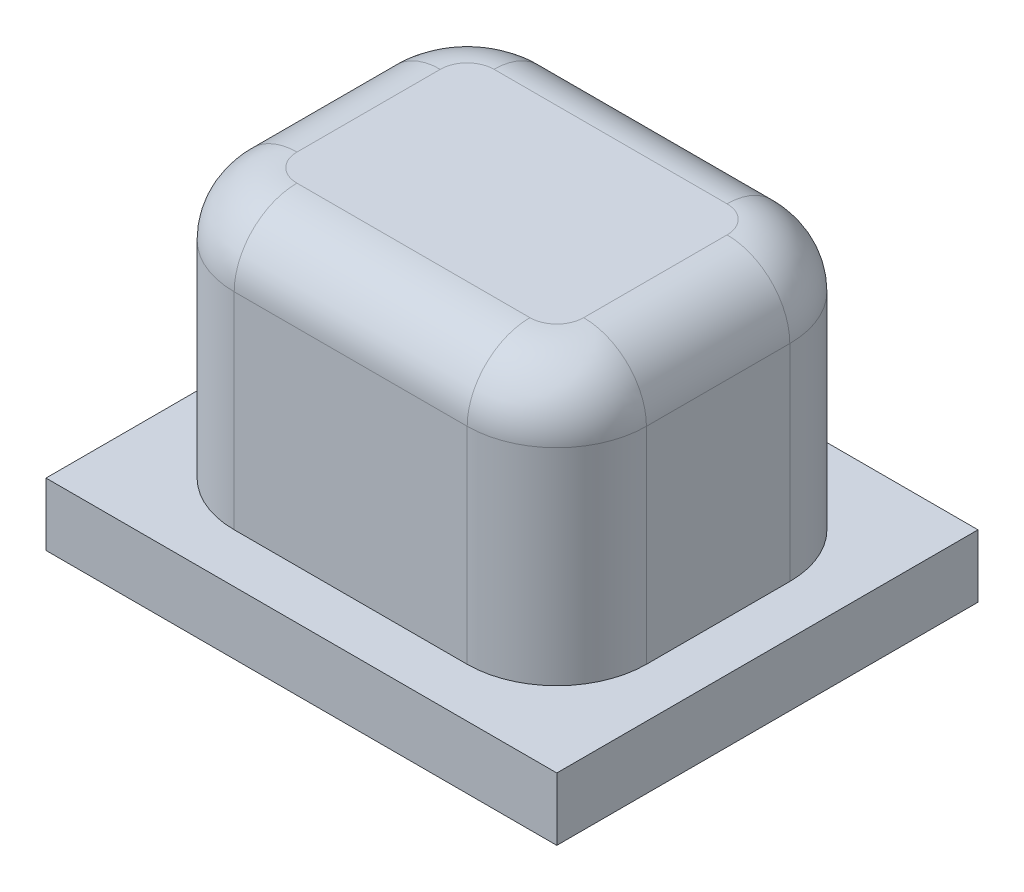
SolidWorks part; units mm, degrees
ref_plane "前视基准面" through (0, 0, 0) normal (0, 0, 1) x (1, 0, 0)
ref_plane "上视基准面" through (0, 0, 0) normal (0, 1, 0) x (1, 0, 0)
ref_plane "右视基准面" through (0, 0, 0) normal (1, 0, 0) x (0, 0, -1)
sketch "草图1" plane through (0, 0, 0) normal (0, 1, 0) x (1, 0, 0)
  line L1 (-1.3, -1.8) -> (1.3, -1.8)
  line L2 (-2.3, -0.8) -> (-2.3, 0.8)
  line L3 (-1.3, 1.8) -> (1.3, 1.8)
  line L4 (2.3, -0.8) -> (2.3, 0.8)
  line L5 (-2.3, -1.8) -> (2.3, 1.8) construction
  line L6 (-2.3, 1.8) -> (2.3, -1.8) construction
  arc A0 (1.3, -1.8) -> (2.3, -0.8) centre (1.3, -0.8) ccw
  arc A1 (-1.3, -1.8) -> (-2.3, -0.8) centre (-1.3, -0.8) cw
  arc A2 (1.3, 1.8) -> (2.3, 0.8) centre (1.3, 0.8) cw
  arc A3 (-2.3, 0.8) -> (-1.3, 1.8) centre (-1.3, 0.8) cw
  point P0 (0, 0)
  dimension "D3" = 1
  dimension "D1" = 4.6
  dimension "D2" = 3.6
extrude "按钮柱体" add sketch "草图1" along normal blind 3
sketch "草图2" plane through (0, 0, 0) normal (0, -1, 0) x (1, 0, 0)
  line L1 (-2.85, -2.35) -> (2.85, -2.35)
  line L2 (-2.85, -2.35) -> (-2.85, 2.35)
  line L3 (-2.85, 2.35) -> (2.85, 2.35)
  line L4 (2.85, -2.35) -> (2.85, 2.35)
  line L5 (-2.85, -2.35) -> (2.85, 2.35) construction
  line L6 (-2.85, 2.35) -> (2.85, -2.35) construction
  point P0 (0, 0)
  dimension "D1" = 5.7
  dimension "D2" = 4.7
extrude "按钮底座" add sketch "草图2" along normal blind 0.7
sketch "草图3" plane through (0, -0.7, 0) normal (0, -1, 0) x (1, 0, 0)
  line L1 (-0.75, -1.25) -> (0.75, -1.25)
  line L2 (-1.75, -0.25) -> (-1.75, 0.25)
  line L3 (-0.75, 1.25) -> (0.75, 1.25)
  line L4 (1.75, -0.25) -> (1.75, 0.25)
  line L5 (-1.75, -1.25) -> (1.75, 1.25) construction
  line L6 (-1.75, 1.25) -> (1.75, -1.25) construction
  arc A1 (0.75, 1.25) -> (1.75, 0.25) centre (0.75, 0.25) cw
  arc A2 (-0.75, -1.25) -> (-1.75, -0.25) centre (-0.75, -0.25) cw
  arc A3 (0.75, -1.25) -> (1.75, -0.25) centre (0.75, -0.25) ccw
  arc A4 (-1.75, 0.25) -> (-0.75, 1.25) centre (-0.75, 0.25) cw
  point P0 (0, 0)
  dimension "D1" = 3.5
  dimension "D3" = 1
  dimension "D2" = 2.5
extrude "底部凹槽" cut sketch "草图3" against normal blind 2.8
fillet "圆角1" radius 0.7 8 edges at (2.0071, 3, -1.5071) (2.3, 3, 0) (2.0071, 3, 1.5071) (0, 3, 1.8) (-2.0071, 3, 1.5071) (-2.3, 3, 0) (-2.0071, 3, -1.5071) (0, 3, -1.8)
